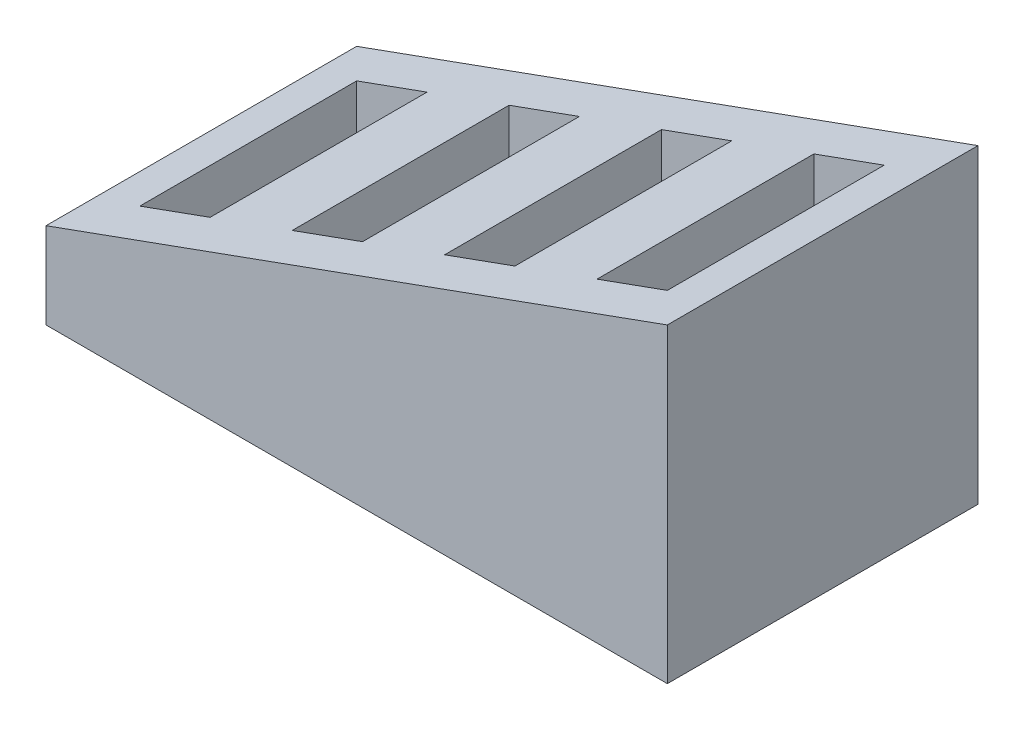
SolidWorks part; units mm, degrees
ref_plane "Front Plane" through (0, 0, 0) normal (0, 0, 1) x (1, 0, 0)
ref_plane "Top Plane" through (0, 0, 0) normal (0, 1, 0) x (1, 0, 0)
ref_plane "Right Plane" through (0, 0, 0) normal (1, 0, 0) x (0, 0, -1)
sketch "Sketch1" plane through (0, 0, 0) normal (0, 0, 1) x (1, 0, 0)
  line L0 (0, 0) -> (-15.9, 0)
  line L2 (0, 7.95) -> (0, 0)
  line L3 (-15.9, 0) -> (-15.9, 2.2)
  line L4 (-15.9, 2.2) -> (0, 7.95)
  dimension "D1" = 7.95
  dimension "D2" = 15.9
  dimension "D3" = 2.2
extrude "Boss-Extrude1" add sketch "Sketch1" against normal blind 7.95
shell "Shell1" thickness 1.2
sketch "Sketch2" plane through (0, 0, 0) normal (0, -1, 0) x (1, 0, 0)
  line L0 (-15.9, -7.95) -> (0, -7.95) construction
  line L1 (-12.9, -6.75) -> (-14.7, -6.75)
  line L2 (-12.9, -6.75) -> (-12.9, -1.2)
  line L3 (-12.9, -1.2) -> (-14.7, -1.2)
  line L4 (-14.7, -6.75) -> (-14.7, -1.2)
  line L5 (-12.9, -6.75) -> (-14.7, -1.2) construction
  line L6 (-12.9, -1.2) -> (-14.7, -6.75) construction
  line L7 (-15.9, -7.95) -> (-15.9, 0) construction
  line L8 (-15.9, 0) -> (0, 0) construction
  point P0 (-13.8, -3.975)
  dimension "D1" = 1.2
  dimension "D2" = 1.2
  dimension "D3" = 1.2
  dimension "D4" = 1.8
extrude "Cut-Extrude1" cut sketch "Sketch2" against normal through all
pattern_linear "LPattern1" count 4 spacing 3.9 along (1, 0, 0) of "Cut-Extrude1"
